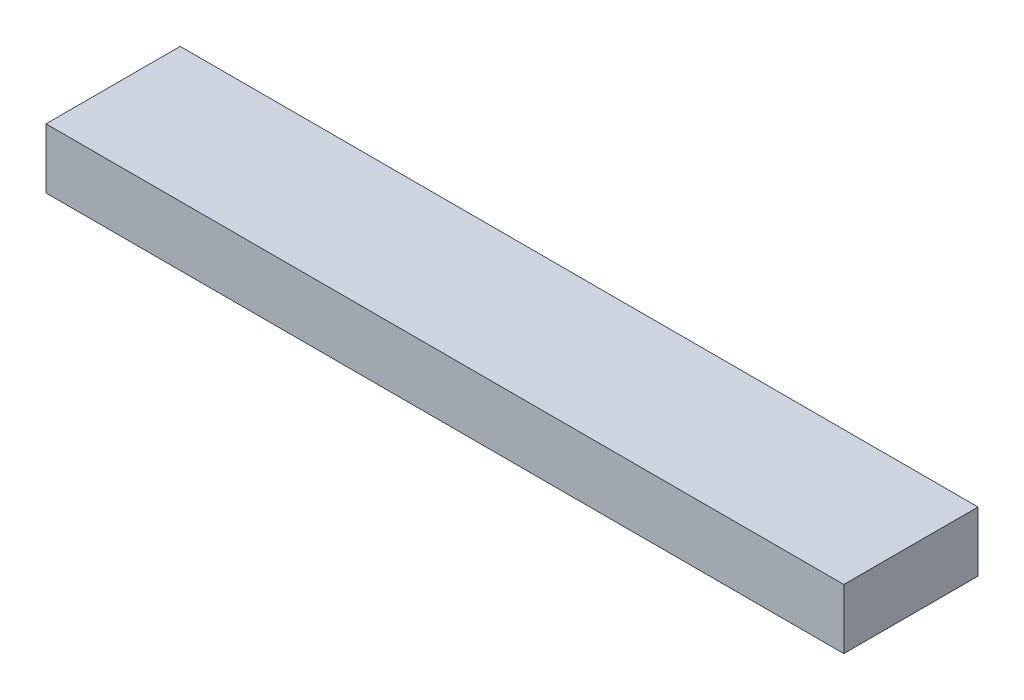
SolidWorks part; units mm, degrees
ref_plane "Front" through (0, 0, 0) normal (0, 0, 1) x (1, 0, 0)
ref_plane "Top" through (0, 0, 0) normal (0, 1, 0) x (1, 0, 0)
ref_plane "Right" through (0, 0, 0) normal (1, 0, 0) x (0, 0, -1)
sketch "Sketch1" plane through (0, 0, 0) normal (0, 0, 1) x (1, 0, 0)
  line L1 (33.3, -2.5) -> (-33.3, -2.5)
  line L2 (33.3, -2.5) -> (33.3, 2.5)
  line L3 (33.3, 2.5) -> (-33.3, 2.5)
  line L4 (-33.3, -2.5) -> (-33.3, 2.5)
  line L5 (33.3, -2.5) -> (-33.3, 2.5) construction
  line L6 (33.3, 2.5) -> (-33.3, -2.5) construction
  point P0 (0, 0)
  dimension "D1" = 66.6
  dimension "D2" = 5
extrude "Boss-Extrude1" add sketch "Sketch1" along normal blind 11.2
